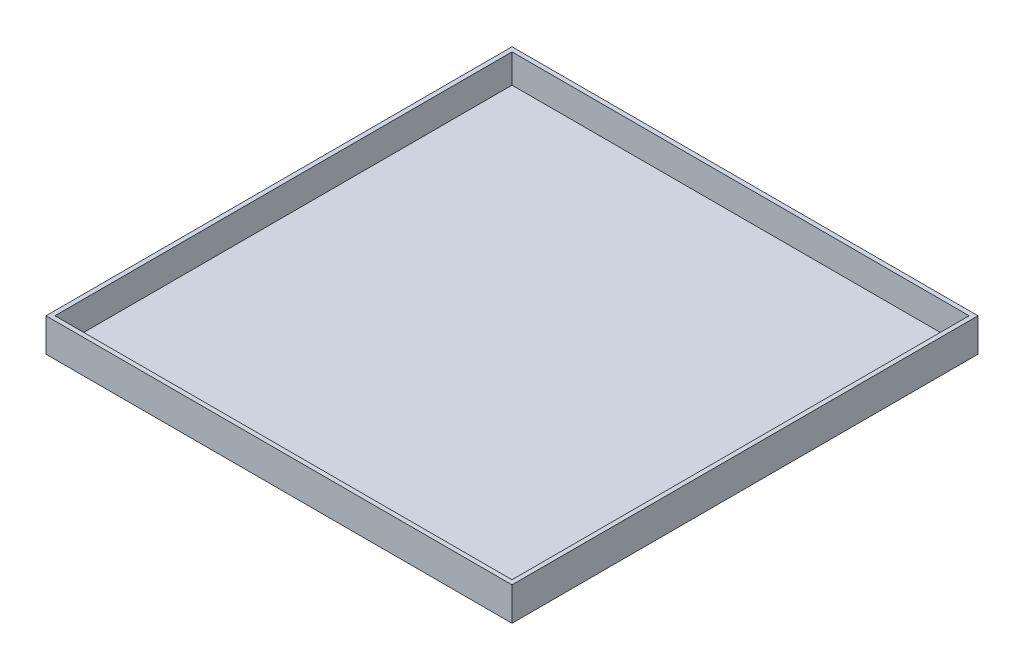
SolidWorks part; units mm, degrees
ref_plane "前视基准面" through (0, 0, 0) normal (0, 0, 1) x (1, 0, 0)
ref_plane "上视基准面" through (0, 0, 0) normal (0, 1, 0) x (1, 0, 0)
ref_plane "右视基准面" through (0, 0, 0) normal (1, 0, 0) x (0, 0, -1)
other "Configuration Table"
sketch "草图1" plane through (0, 0, 0) normal (0, 1, 0) x (1, 0, 0)
  line L1 (0, 0) -> (210, 0)
  line L2 (0, 0) -> (0, 210)
  line L3 (0, 210) -> (210, 210)
  line L4 (210, 0) -> (210, 210)
  dimension "D1" = 210
  dimension "D2" = 210
extrude "凸台-拉伸1" add sketch "草图1" along normal blind 15
shell "抽壳1" thickness 2
